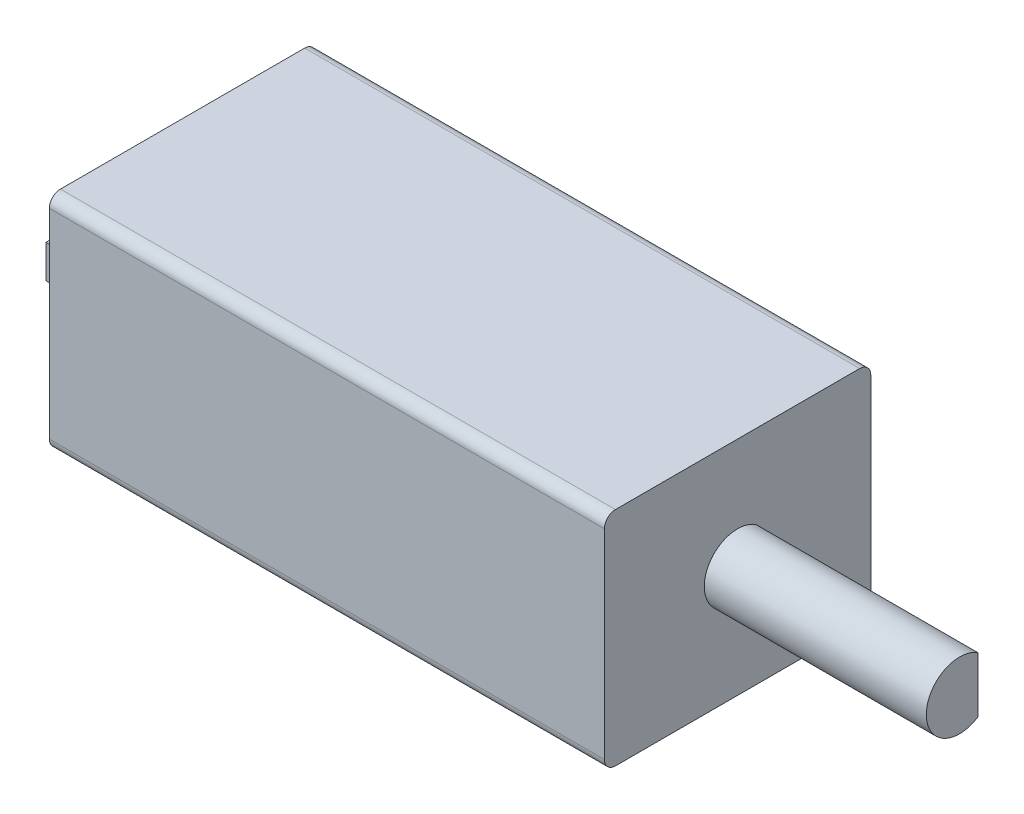
SolidWorks part; units mm, degrees
ref_plane "前视基准面" through (0, 0, 0) normal (0, 0, 1) x (1, 0, 0)
ref_plane "上视基准面" through (0, 0, 0) normal (0, 1, 0) x (1, 0, 0)
ref_plane "右视基准面" through (0, 0, 0) normal (1, 0, 0) x (0, 0, -1)
sketch "草图1" plane through (0, 0, 0) normal (1, 0, 0) x (0, 0, -1)
  line L1 (-5.5, 5) -> (5.5, 5)
  line L2 (-6, 4.5) -> (-6, -4.5)
  line L3 (-5.5, -5) -> (5.5, -5)
  line L4 (6, 4.5) -> (6, -4.5)
  line L5 (-6, 5) -> (6, -5) construction
  line L6 (-6, -5) -> (6, 5) construction
  arc A0 (6, 4.5) -> (5.5, 5) centre (5.5, 4.5) ccw
  arc A1 (5.5, -5) -> (6, -4.5) centre (5.5, -4.5) ccw
  arc A2 (-6, -4.5) -> (-5.5, -5) centre (-5.5, -4.5) ccw
  arc A3 (-6, 4.5) -> (-5.5, 5) centre (-5.5, 4.5) cw
  point P0 (0, 0)
  dimension "D3" = 0.5
  dimension "D1" = 10
  dimension "D2" = 12
extrude "凸台-拉伸1" add sketch "草图1" along normal blind 25
sketch "草图2" plane through (25, 0, 0) normal (1, 0, 0) x (0, 0, -1)
  line L0 (0, 5) -> (0, -5) construction
  line L1 (1.0333, -1.0873) -> (0.8292, -1.25)
  line L2 (0.8292, -1.25) -> (0.8292, 1.25)
  line L4 (5.5, 5) -> (-5.5, 5)
  line L5 (-6, 4.5) -> (-6, -4.5)
  line L6 (-5.5, -5) -> (5.5, -5)
  line L7 (6, -4.5) -> (6, 4.5)
  line L8 (5.5, 5) -> (-5.5, 5)
  line L9 (-6, 4.5) -> (-6, -4.5)
  line L10 (-5.5, -5) -> (5.5, -5)
  line L11 (6, -4.5) -> (6, 4.5)
  circle A0 centre (0, 0) radius 1.5
  arc A4 (6, 4.5) -> (5.5, 5) centre (5.5, 4.5) ccw
  arc A5 (-5.5, 5) -> (-6, 4.5) centre (-5.5, 4.5) ccw
  arc A6 (-6, -4.5) -> (-5.5, -5) centre (-5.5, -4.5) ccw
  arc A7 (5.5, -5) -> (6, -4.5) centre (5.5, -4.5) ccw
  arc A8 (6, 4.5) -> (5.5, 5) centre (5.5, 4.5) ccw
  arc A9 (-5.5, 5) -> (-6, 4.5) centre (-5.5, 4.5) ccw
  arc A10 (-6, -4.5) -> (-5.5, -5) centre (-5.5, -4.5) ccw
  arc A11 (5.5, -5) -> (6, -4.5) centre (5.5, -4.5) ccw
  dimension "D2" = 3
  dimension "D3" = 2.5
  dimension "D1" = 0
extrude "凸台-拉伸2" add sketch "草图2" along normal blind 10 contours A0 L0 L2 | L0 A0
sketch "草图3" plane through (0, 0, 0) normal (-1, 0, 0) x (0, 0, 1)
  line L0 (6, 0) -> (-6, 0) construction
  line L1 (0, -5) -> (0, 5) construction
  line L2 (-3.65, -0.75) -> (-3.35, -0.75)
  line L3 (3.65, 0.75) -> (3.35, 0.75)
  line L4 (-6, 4.5) -> (-6, -4.5)
  line L5 (-5.5, -5) -> (5.5, -5)
  line L6 (6, -4.5) -> (6, 4.5)
  line L7 (5.5, 5) -> (-5.5, 5)
  line L8 (-6, 4.5) -> (-6, -4.5)
  line L9 (-5.5, -5) -> (5.5, -5)
  line L10 (6, -4.5) -> (6, 4.5)
  line L11 (5.5, 5) -> (-5.5, 5)
  line L12 (3.65, 0.75) -> (3.65, -0.75)
  line L13 (3.65, -0.75) -> (3.35, -0.75)
  line L14 (3.35, 0.75) -> (3.35, -0.75)
  line L15 (3.65, 0.75) -> (3.35, -0.75) construction
  line L16 (3.65, -0.75) -> (3.35, 0.75) construction
  line L17 (-3.65, 0.75) -> (-3.65, -0.75)
  line L18 (-3.65, 0.75) -> (-3.35, 0.75)
  line L19 (-3.35, 0.75) -> (-3.35, -0.75)
  arc A4 (-5.5, 5) -> (-6, 4.5) centre (-5.5, 4.5) ccw
  arc A5 (-6, -4.5) -> (-5.5, -5) centre (-5.5, -4.5) ccw
  arc A6 (5.5, -5) -> (6, -4.5) centre (5.5, -4.5) ccw
  arc A7 (6, 4.5) -> (5.5, 5) centre (5.5, 4.5) ccw
  arc A8 (-5.5, 5) -> (-6, 4.5) centre (-5.5, 4.5) ccw
  arc A9 (-6, -4.5) -> (-5.5, -5) centre (-5.5, -4.5) ccw
  arc A10 (5.5, -5) -> (6, -4.5) centre (5.5, -4.5) ccw
  arc A11 (6, 4.5) -> (5.5, 5) centre (5.5, 4.5) ccw
  point P15 (3.5, 0)
  dimension "D2" = 0.3
  dimension "D3" = 1.5
  dimension "D4" = 7.3
  dimension "D1" = 0
extrude "凸台-拉伸3" add sketch "草图3" along normal blind 2.5 contours L12 L13 L14 L3 | L19 L2 L17 L18
